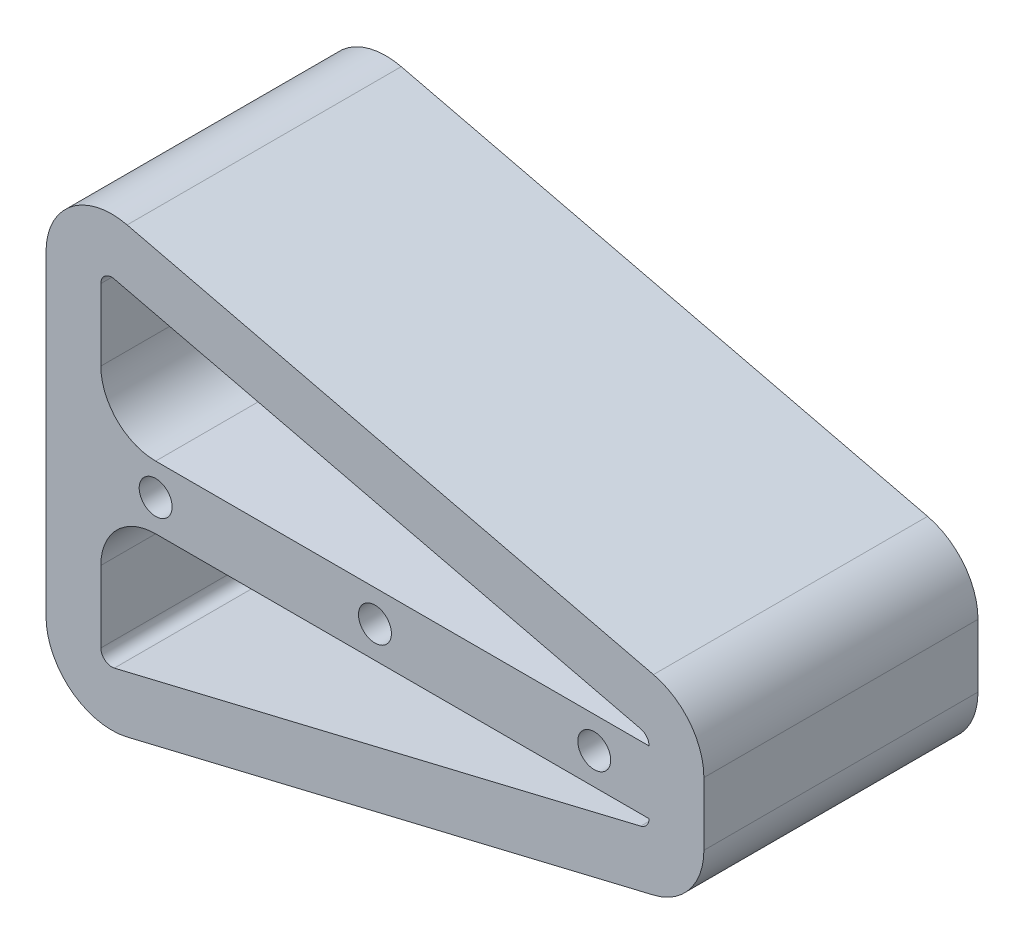
SolidWorks part; units mm, degrees
ref_plane "Front Plane" through (0, 0, 0) normal (0, 0, 1) x (1, 0, 0)
ref_plane "Top Plane" through (0, 0, 0) normal (0, 1, 0) x (1, 0, 0)
ref_plane "Right Plane" through (0, 0, 0) normal (1, 0, 0) x (0, 0, -1)
sketch "Sketch1" plane through (0, 0, 0) normal (0, 0, 1) x (1, 0, 0)
  line L0 (0, 0) -> (150, 0) construction
  line L1 (11.6667, 48.6198) -> (153.5, 14.586) construction
  line L2 (11.6667, -48.6198) -> (153.5, -14.586) construction
  line L3 (9.3333, 38.8959) -> (151.1667, 4.862)
  line L4 (9.3333, -38.8959) -> (151.1667, -4.862)
  line L5 (45, 14.3899) -> (45, -14.3899)
  line L6 (105, 2.872) -> (105, -2.872)
  line L7 (52.4, 20.2243) -> (100.4, 8.7064)
  line L8 (52.4, -20.2243) -> (100.4, -8.7064)
  line L9 (51.2333, 15.3623) -> (99.2333, 3.8444)
  line L11 (51.2333, -15.3623) -> (99.2333, -3.8444)
  line L12 (50, 14.3899) -> (50, 2.872)
  line L13 (50, 2.872) -> (100, 2.872)
  line L14 (50, -2.872) -> (100, -2.872)
  line L15 (50, -2.872) -> (50, -14.3899)
  line L16 (50, 14.3899) -> (50, -14.3899) construction
  line L17 (100, 2.872) -> (100, -2.872) construction
  arc A0 (11.6667, 48.6198) -> (11.6667, -48.6198) centre (0, 0) ccw construction
  arc A1 (153.5, -14.586) -> (153.5, 14.586) centre (150, 0) ccw construction
  circle A2 centre (0, 0) radius 4 construction
  circle A3 centre (150, 0) radius 4 construction
  circle A4 centre (0, 0) radius 15 construction
  circle A5 centre (15, 0) radius 1.5 construction
  circle A6 centre (0, 15) radius 1.5 construction
  circle A7 centre (-15, 0) radius 1.5 construction
  circle A8 centre (0, -15) radius 1.5 construction
  arc A9 (151.1667, -4.862) -> (151.1667, 4.862) centre (150, 0) ccw
  arc A10 (9.3333, 38.8959) -> (9.3333, -38.8959) centre (0, 0) ccw
  arc A11 (100.4, 8.7064) -> (105, 2.872) centre (99, 2.872) cw
  arc A12 (100.4, -8.7064) -> (105, -2.872) centre (99, -2.872) ccw
  arc A13 (52.4, -20.2243) -> (45, -14.3899) centre (51, -14.3899) cw
  arc A14 (52.4, 20.2243) -> (45, 14.3899) centre (51, 14.3899) ccw
  arc A15 (99.2333, 3.8444) -> (100, 2.872) centre (99, 2.872) cw
  arc A16 (99.2333, -3.8444) -> (100, -2.872) centre (99, -2.872) ccw
  arc A17 (51.2333, -15.3623) -> (50, -14.3899) centre (51, -14.3899) cw
  arc A18 (51.2333, 15.3623) -> (50, 14.3899) centre (51, 14.3899) ccw
  circle A19 centre (75, 0) radius 1.5
  circle A20 centre (95, 0) radius 1.5
  circle A21 centre (55, 0) radius 1.5
  point P30 (105, 7.6026)
  point P33 (105, -7.6026)
  point P36 (45, -22)
  point P39 (45, 22)
  dimension "D1" = 100
  dimension "D2" = 30
  dimension "D4" = 8
  dimension "D5" = 8
  dimension "D6" = 30
  dimension "D7" = 3
  dimension "D12" = 6
  dimension "D14" = 3
  dimension "D15" = 3
  dimension "D16" = 3
  dimension "D3" = 150
  dimension "D9" = 45
  dimension "D10" = 45
  dimension "D11" = 22
  dimension "D17" = 20
  dimension "D18" = 20
  dimension "D8" = 10
  dimension "D13" = 5
extrude "Boss-Extrude1" add sketch "Sketch1" along normal blind 25 contours L7 A14 L5 A13 L8 A12 L6 A11 A18 L9 A15 L13 L12 L11 A17 L15 L14 A16
fillet "Fillet1" radius 5 2 edges at (50, -2.872, 12.5) (50, 2.872, 12.5)
